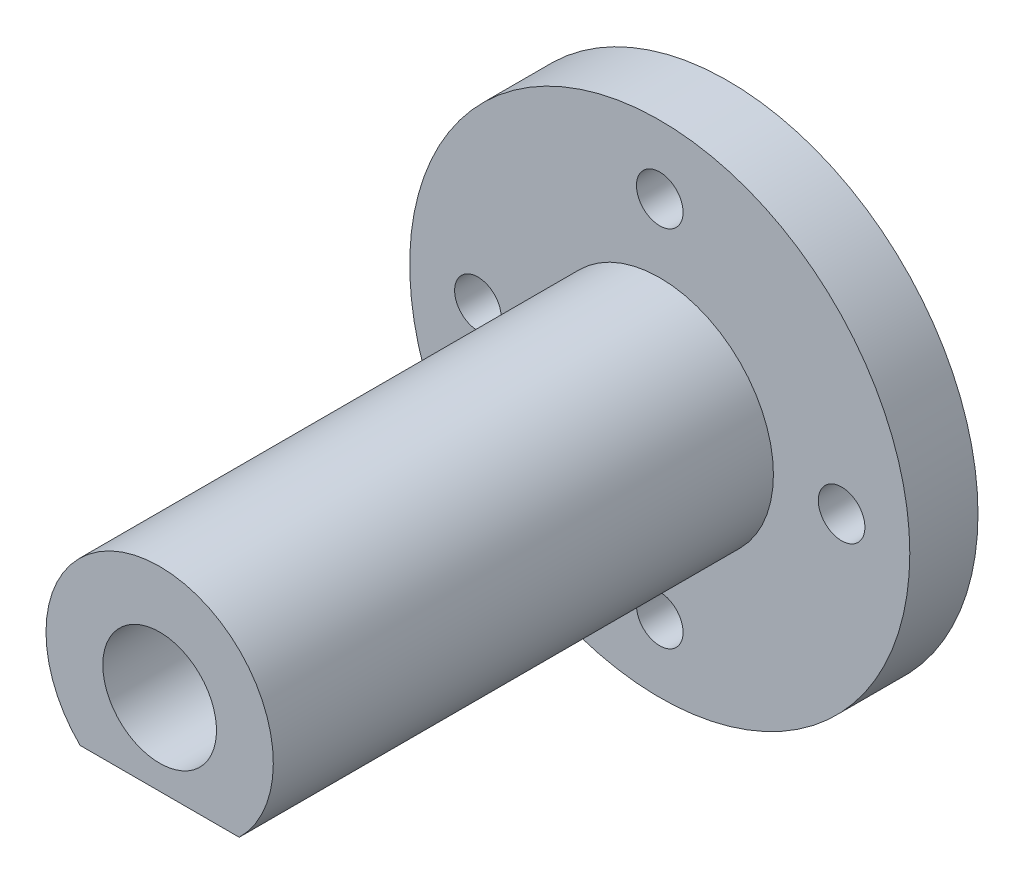
SolidWorks part; units mm, degrees
material "6061 Alloy"
ref_plane "Front Plane" through (0, 0, 0) normal (1, 0, 0) x (0, 1, 0)
ref_plane "Top Plane" through (0, 0, 0) normal (0, 0, 1) x (0, 1, 0)
ref_plane "Right Plane" through (0, 0, 0) normal (0, 1, 0) x (-1, 0, 0)
sketch "Sketch1" plane through (0, 0, 0) normal (0, 0, 1) x (0, 1, 0)
  line L0 (0, 8) -> (0, 0) construction
  circle A0 centre (0, 0) radius 11
  circle A1 centre (0, 8) radius 1.025
  circle A2 centre (0, 0) radius 4.25
  circle A3 centre (8, 0) radius 1.025
  circle A4 centre (0, -8) radius 1.025
  circle A5 centre (-8, 0) radius 1.025
  point P15 (0, 0)
  dimension "D1" = 22
  dimension "D2" = 8
  dimension "D3" = 2.05
  dimension "D4" = 8.5
  dimension "D5" = 4
extrude "Boss-Extrude1" add sketch "Sketch1" along normal blind 3
sketch "Sketch2" plane through (0, 0, 3) normal (0, 0, 1) x (1, 0, 0)
  circle A1 centre (0, 0) radius 5
  circle A2 centre (0, 0) radius 2.5
  dimension "D1" = 5
  dimension "D2" = 10
extrude "Boss-Extrude2" add sketch "Sketch2" along normal offset from surface (22 mm away) 25 up to face at (11, 0, 0)
sketch "Sketch3" plane through (0, 0, 25) normal (0, 0, 1) x (1, 0, 0)
  line L0 (3.5, -3.5707) -> (-3.5, -3.5707)
  circle A0 centre (0, 0) radius 5 construction
  circle A1 centre (0, 0) radius 5 construction
  arc A2 (-3.5, -3.5707) -> (3.5, -3.5707) centre (0, 0) ccw
  dimension "D1" = 7
extrude "Cut-Extrude1" cut sketch "Sketch3" against normal blind 10
